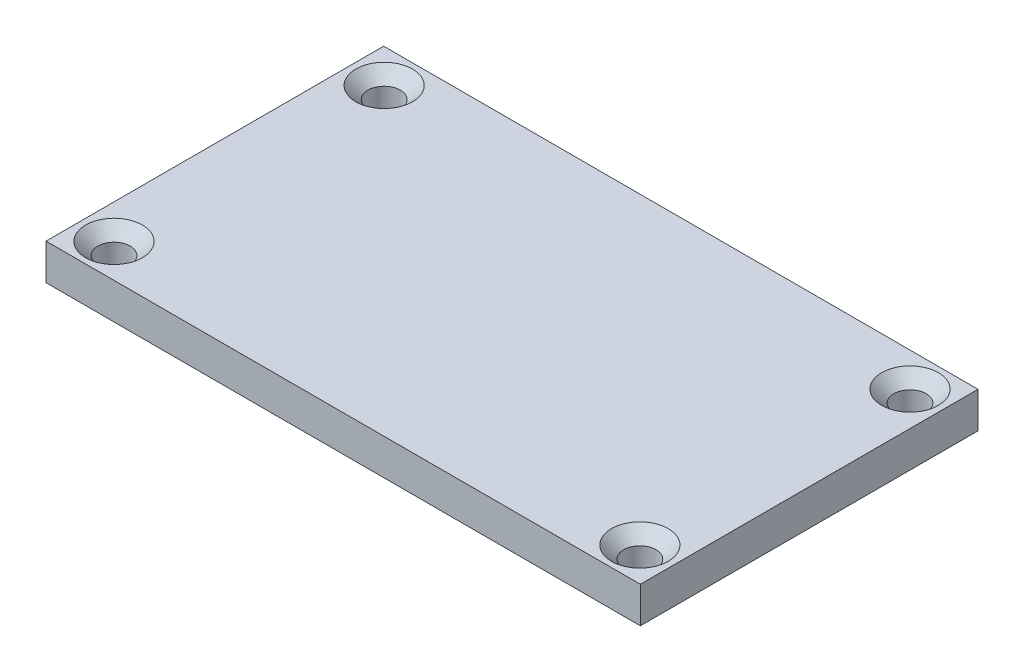
SolidWorks part; units mm, degrees
material "1.0503 (C45)"
ref_plane "Front Plane" through (0, 0, 0) normal (0, 0, 1) x (1, 0, 0)
ref_plane "Top Plane" through (0, 0, 0) normal (0, 1, 0) x (1, 0, 0)
ref_plane "Right Plane" through (0, 0, 0) normal (1, 0, 0) x (0, 0, -1)
sketch "Sketch1" plane through (0, 0, 0) normal (0, 1, 0) x (1, 0, 0)
  line L1 (-33, -18.75) -> (33, -18.75)
  line L2 (-33, -18.75) -> (-33, 18.75)
  line L3 (-33, 18.75) -> (33, 18.75)
  line L4 (33, -18.75) -> (33, 18.75)
  line L5 (-33, -18.75) -> (33, 18.75) construction
  line L6 (-33, 18.75) -> (33, -18.75) construction
  point P0 (0, 0)
  dimension "D1" = 66
  dimension "D2" = 37.5
extrude "Boss-Extrude1" add sketch "Sketch1" along normal mid plane 4
hole_wizard "CSK for M3 Countersunk Flat Head Screw1" positions "Sketch2" profile "Sketch3" countersink size "M3" standard "ISO"
sketch "Sketch2" plane through (0, 2, 0) normal (0, 1, 0) x (1, 0, 0)
  line L0 (-33, 18.75) -> (-33, -18.75) construction
  line L2 (-55, 0) -> (55, 0) construction
  line L3 (33, -18.75) -> (33, 18.75) construction
  point P0 (-29.2, -15)
  point P2 (-29.2, 15)
  point P4 (29.2, 15)
  point P6 (29.2, -15)
  dimension "D1" = 3.8
  dimension "D2" = 3.8
  dimension "D3" = 15
  dimension "D4" = 30
sketch "Sketch3" plane through (-29.2, 2, 15) normal (1, 0, 0) x (0, 0, 1)
  line L0 (0, 0) -> (0, 6.0815)
  line L1 (0, 6.0815) -> (1.8, 5)
  line L2 (1.8, 5) -> (1.8, 1.35)
  line L3 (1.8, 1.35) -> (3.15, 0)
  line L5 (3.15, 0) -> (0, 0)
  line L6 (-1.8, 1.35) -> (-3.15, 0) construction
  line L10 (0, 6.0815) -> (-1.8, 5) construction
  line L11 (0, -6.35) -> (0, 107.95) construction
  dimension "Hole Dia." = 3.6
  dimension "Hole Depth" = 5
  dimension "Near C'Sink Dia." = 6.3
  dimension "Near C'Sink Angle" = 90
  dimension "Drill Angle" = 118
